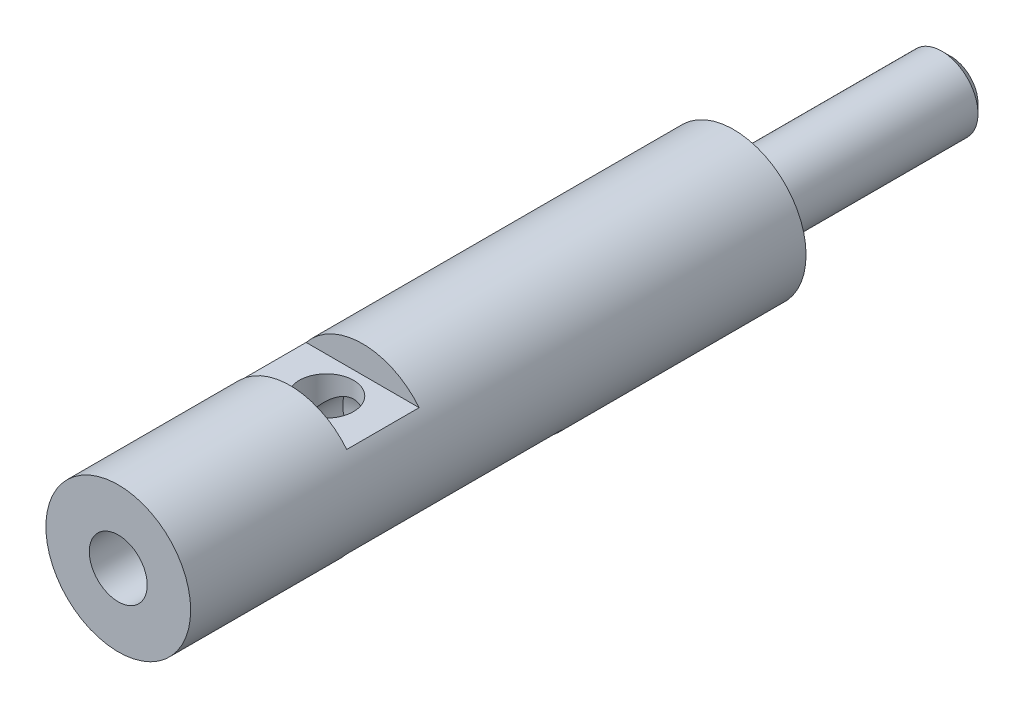
SolidWorks part; units mm, degrees
ref_plane "Front Plane" through (0, 0, 0) normal (0, 0, 1) x (1, 0, 0)
ref_plane "Top Plane" through (0, 0, 0) normal (0, 1, 0) x (1, 0, 0)
ref_plane "Right Plane" through (0, 0, 0) normal (1, 0, 0) x (0, 0, -1)
sketch "Sketch1" plane through (0, 0, 0) normal (0, 0, 1) x (1, 0, 0)
  circle A0 centre (0, 0) radius 4
  dimension "D1" = 8
extrude "Boss-Extrude1" add sketch "Sketch1" against normal blind 34
sketch "Sketch2" plane through (0, 0, -34) normal (0, 0, -1) x (-1, 0, 0)
  circle A0 centre (0, 0) radius 2
  dimension "D1" = 4
extrude "Boss-Extrude2" add sketch "Sketch2" along normal blind 12
chamfer "Chamfer1" distance 0.5 angle 45 1 edges at (-2, 0, -46)
hole_wizard "Ø3.2 (3.2) Diameter Hole1" positions "Sketch3" profile "Sketch4" hole size "Ø3.2" standard "ANSI Metric"
sketch "Sketch3" plane through (0, 0, 0) normal (0, 0, 1) x (1, 0, 0)
  point P0 (0, 0)
sketch "Sketch4" plane through (0, 0, 0) normal (1, 0, 0) x (0, -1, 0)
  line L0 (0, 0) -> (0, 14.9614)
  line L1 (0, 14.9614) -> (1.6, 14)
  line L2 (1.6, 14) -> (1.6, 0)
  line L5 (1.6, 0) -> (0, 0)
  line L10 (0, 14.9614) -> (-1.6, 14) construction
  line L11 (0, -6.35) -> (0, 107.95) construction
  dimension "Hole Dia." = 3.2
  dimension "Hole Depth" = 14
  dimension "Drill Angle" = 118
sketch "Sketch5" plane through (0, 0, 0) normal (1, 0, 0) x (0, 0, -1)
  line L0 (0, -4) -> (34, -4) construction
  line L1 (9.5, -4) -> (21.5, -4)
  line L2 (9.5, -4) -> (9.5, -2.5)
  line L3 (9.5, -2.5) -> (21.5, -2.5)
  line L4 (21.5, -4) -> (21.5, -2.5)
  line L5 (34, 4) -> (0, 4) construction
  line L6 (9.5, 4) -> (13.5, 4)
  line L7 (9.5, 4) -> (9.5, 2.5)
  line L8 (9.5, 2.5) -> (13.5, 2.5)
  line L9 (13.5, 4) -> (13.5, 2.5)
  line L10 (0, 4) -> (0, -4) construction
  dimension "D1" = 1.5
  dimension "D2" = 12
  dimension "D3" = 1.5
  dimension "D4" = 4
  dimension "D5" = 9.5
extrude "Cut-Extrude2" cut sketch "Sketch5" against normal through all both and the other way through all contours L3 L4 L1 L2 | L8 L9 L6 L7
hole_wizard "Ø3.0 (3) Diameter Hole1" positions "Sketch8" profile "Sketch9" hole size "Ø3.0" standard "ANSI Metric"
sketch "Sketch8" plane through (0, 2.5, 0) normal (0, 1, 0) x (1, 0, 0)
  line L0 (-3.1225, 9.5) -> (3.1225, 13.5) construction
  point P7 (0, 11.5)
sketch "Sketch9" plane through (0, 2.5, -11.5) normal (1, 0, 0) x (0, 0, 1)
  line L0 (0, 0) -> (0, 0.9)
  line L1 (0, 0.9) -> (1.5, 0.9)
  line L2 (1.5, 0.9) -> (1.5, 0)
  line L5 (1.5, 0) -> (0, 0)
  line L11 (0, -6.35) -> (0, 107.95) construction
  dimension "Thru Hole Dia." = 3
  dimension "Thru Hole Depth" = 0.9
